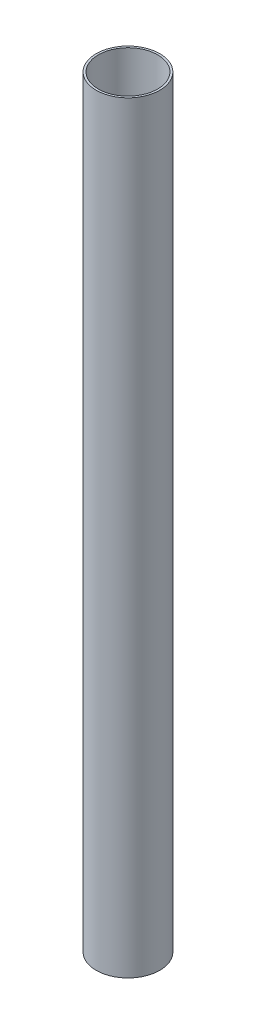
SolidWorks part; units mm, degrees
ref_plane "Front Plane" through (0, 0, 0) normal (0, 0, 1) x (1, 0, 0)
ref_plane "Top Plane" through (0, 0, 0) normal (0, 1, 0) x (1, 0, 0)
ref_plane "Right Plane" through (0, 0, 0) normal (1, 0, 0) x (0, 0, -1)
sketch "Sketch1" plane through (0, 0, 0) normal (0, 1, 0) x (1, 0, 0)
  circle A0 centre (0, 0) radius 25.4
  circle A1 centre (0, 0) radius 23.749
  dimension "D1" = 1.651
  dimension "D2" = 50.8
extrude "Boss-Extrude1" add sketch "Sketch1" along normal blind 609.6
